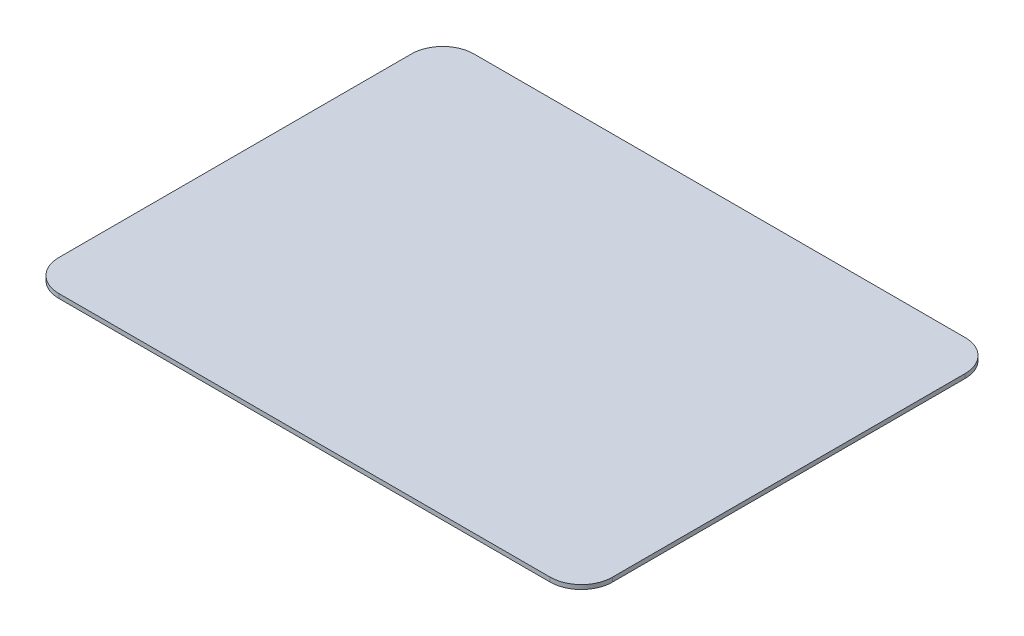
SolidWorks part; units mm, degrees
material "6061-T6 (SS)"
ref_plane "Front Plane" through (0, 0, 0) normal (0, 0, 1) x (1, 0, 0)
ref_plane "Top Plane" through (0, 0, 0) normal (0, 1, 0) x (1, 0, 0)
ref_plane "Right Plane" through (0, 0, 0) normal (1, 0, 0) x (0, 0, -1)
sketch "Sketch1" plane through (0, 0, 0) normal (0, 1, 0) x (1, 0, 0)
  line L1 (-146.6469, 109.9312) -> (146.6469, 109.9312)
  line L2 (-146.6469, 109.9312) -> (-146.6469, -109.9312)
  line L3 (-146.6469, -109.9312) -> (146.6469, -109.9312)
  line L4 (146.6469, 109.9312) -> (146.6469, -109.9312)
  line L5 (-146.6469, 109.9312) -> (146.6469, -109.9312) construction
  line L6 (-146.6469, -109.9312) -> (146.6469, 109.9312) construction
  point P0 (0, 0)
  dimension "D1" = 293.2938
  dimension "D2" = 219.8624
extrude "Boss-Extrude1" add sketch "Sketch1" along normal blind 2.286
fillet "Fillet1" radius 16.51 4 edges at (-146.6469, 1.143, -109.9312) (146.6469, 1.143, -109.9312) (-146.6469, 1.143, 109.9312) (146.6469, 1.143, 109.9312)
